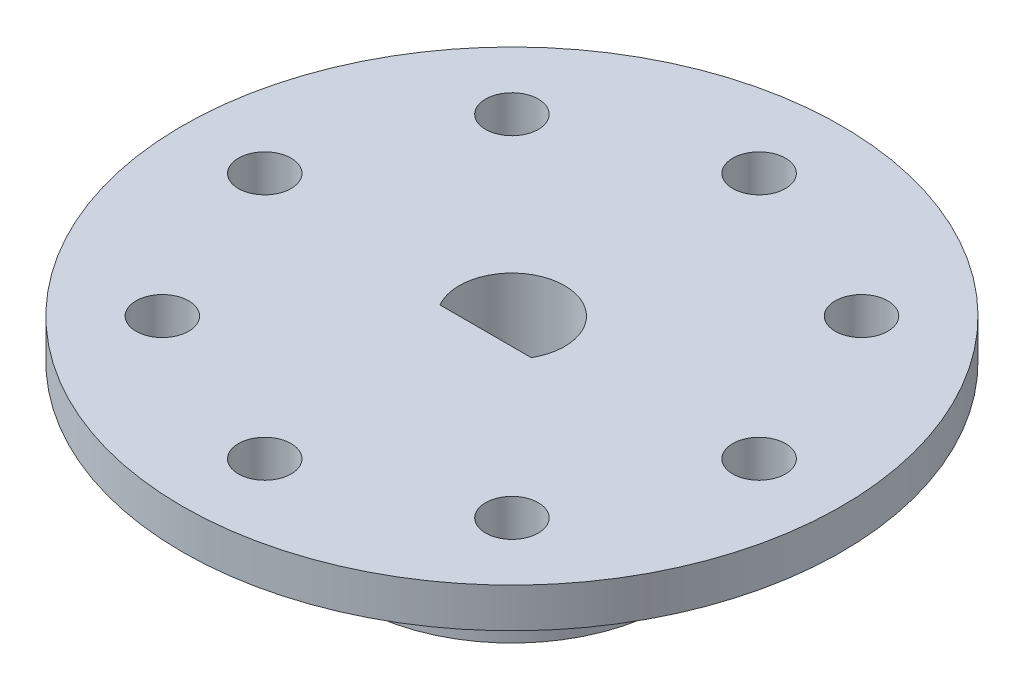
SolidWorks part; units mm, degrees
ref_plane "前视基准面" through (0, 0, 0) normal (0, 0, 1) x (1, 0, 0)
ref_plane "上视基准面" through (0, 0, 0) normal (0, 1, 0) x (1, 0, 0)
ref_plane "右视基准面" through (0, 0, 0) normal (1, 0, 0) x (0, 0, -1)
other "Configuration Table"
sketch "草图1" plane through (0, 0, 0) normal (0, 1, 0) x (1, 0, 0)
  line L0 (-1000, 0) -> (49000, 0) construction
  line L1 (0, -999.2745) -> (0, 49000.7255) construction
  line L2 (-706.8891, -706.8891) -> (34648.4499, 34648.4499) construction
  circle A0 centre (0, 0) radius 25
  circle A1 centre (0, 0) radius 18.75 construction
  circle A2 centre (-18.75, 0) radius 2
  circle A3 centre (0, -18.75) radius 2
  circle A4 centre (-13.2583, -13.2583) radius 2
  circle A5 centre (0, 18.75) radius 2
  circle A6 centre (-13.2583, 13.2583) radius 2
  circle A7 centre (13.2583, 13.2583) radius 2
  circle A8 centre (18.75, 0) radius 2
  circle A9 centre (13.2583, -13.2583) radius 2
  point P16 (-13.2583, -13.2583)
  dimension "D1" = 50
  dimension "D2" = 37.5
  dimension "D4" = 4
  dimension "D5" = 4
  dimension "D3" = 45
extrude "凸台-拉伸1" add sketch "草图1" along normal blind 3
sketch "草图2" plane through (0, 0, 0) normal (0, -1, 0) x (1, 0, 0)
  circle A0 centre (0, 0) radius 12
  dimension "D1" = 24
extrude "凸台-拉伸2" add sketch "草图2" along normal blind 10 contours A0
sketch "草图3" plane through (0, -10, 0) normal (0, -1, 0) x (1, 0, 0)
  line L0 (-3.4641, 2) -> (3.4641, 2)
  arc A0 (-3.4641, 2) -> (3.4641, 2) centre (0, 0) ccw
  dimension "D1" = 4
  dimension "D2" = 2
extrude "切除-拉伸1" cut sketch "草图3" against normal through all
sketch "草图4" plane through (0, 0, 2) normal (0, 0, -1) x (-1, 0, 0)
  line L0 (0, 0) -> (0, -10) construction
  line L1 (-3.4641, -10) -> (3.4641, -10) construction
  circle A0 centre (0, -5) radius 1.5
  dimension "D1" = 3
extrude "切除-拉伸2" cut sketch "草图4" against normal through all
